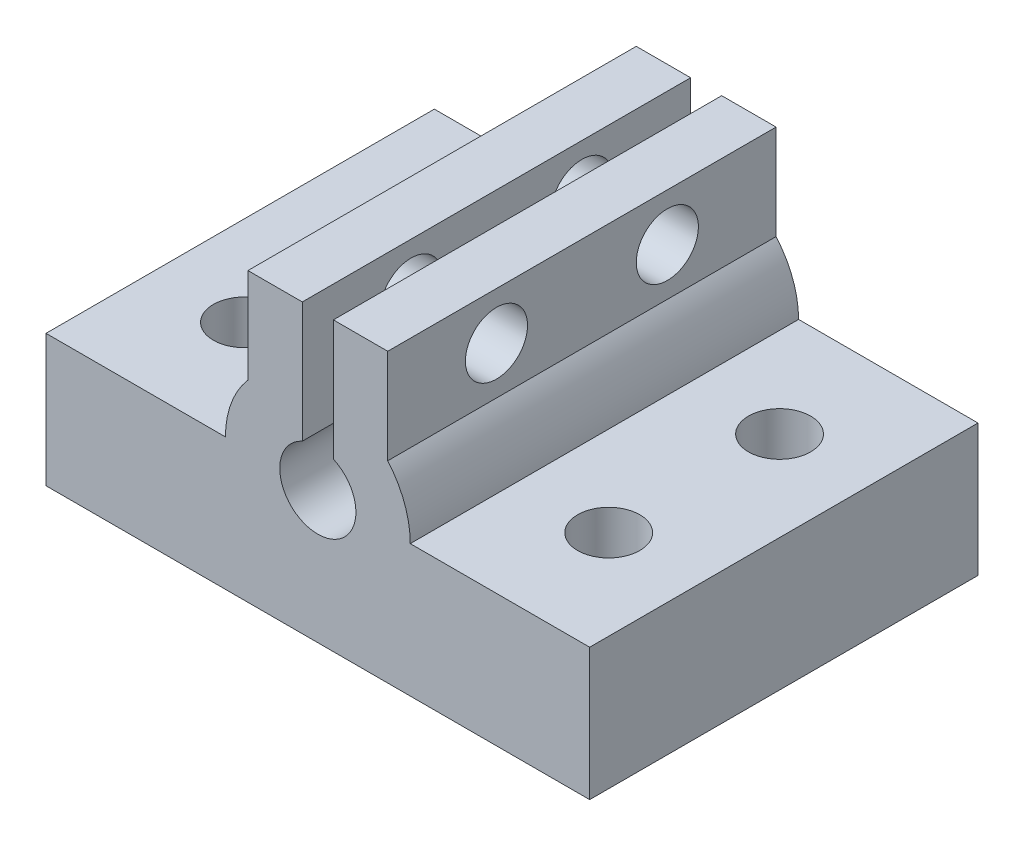
SolidWorks part; units mm, degrees
ref_plane "Front Plane" through (0, 0, 0) normal (0, 0, 1) x (1, 0, 0)
ref_plane "Top Plane" through (0, 0, 0) normal (0, 1, 0) x (1, 0, 0)
ref_plane "Right Plane" through (0, 0, 0) normal (1, 0, 0) x (0, 0, -1)
sketch "Sketch1" plane through (0, 0, 0) normal (0, 0, 1) x (1, 0, 0)
  line L0 (0, 0) -> (35, 0)
  line L1 (35, 0) -> (35, 8.5)
  line L2 (35, 8.5) -> (23.45, 8.5)
  line L3 (11.55, 8.5) -> (0, 8.5)
  line L4 (0, 8.5) -> (0, 0)
  line L5 (13, 12.3926) -> (13, 18.5)
  line L6 (13, 18.5) -> (16.5, 18.5)
  line L7 (16.5, 18.5) -> (16.5, 10.7366)
  line L8 (17.5, 0) -> (17.5, 18.5) construction
  line L9 (18.5, 10.7366) -> (18.5, 18.5)
  line L10 (18.5, 18.5) -> (22, 18.5)
  line L11 (22, 18.5) -> (22, 12.3926)
  arc A0 (23.45, 8.5) -> (22, 12.3926) centre (17.5, 8.5) ccw
  arc A1 (13, 12.3926) -> (11.55, 8.5) centre (17.5, 8.5) ccw
  arc A2 (16.5, 10.7366) -> (18.5, 10.7366) centre (17.5, 8.5) ccw
  dimension "D1" = 4.9
  dimension "D4" = 10
  dimension "D6" = 3.5
  dimension "D2" = 35
  dimension "D3" = 8.5
  dimension "D5" = 3.5
  dimension "D7" = 2
extrude "Boss-Extrude1" add sketch "Sketch1" along normal blind 25
sketch "Sketch2" plane through (22, 0, 0) normal (1, 0, 0) x (0, 0, -1)
  line L0 (-25, 15.4463) -> (0, 15.4463) construction
  line L1 (-25, 12.3926) -> (-25, 18.5) construction
  line L2 (0, 12.3926) -> (0, 18.5) construction
  circle A0 centre (-18, 15.4463) radius 2
  circle A1 centre (-7, 15.4463) radius 2
  dimension "D3" = 4
  dimension "D1" = 7
  dimension "D2" = 7
extrude "Cut-Extrude1" cut sketch "Sketch2" against normal up to surface (9 mm away) up to face at (13, 15.4463, 12.5)
sketch "Sketch3" plane through (0, 8.5, 0) normal (0, 1, 0) x (1, 0, 0)
  line L0 (29.225, -25) -> (29.225, 0) construction
  line L1 (35, -25) -> (23.45, -25) construction
  line L2 (35, 0) -> (23.45, 0) construction
  line L3 (17.5, -25) -> (17.5, 0) construction
  line L4 (0, 0) -> (35, 0) construction
  line L5 (0, -25) -> (35, -25) construction
  circle A0 centre (29.225, -18) radius 2
  circle A1 centre (29.225, -7) radius 2
  circle A2 centre (5.775, -7) radius 2
  circle A3 centre (5.775, -18) radius 2
  dimension "D2" = 7
  dimension "D3" = 4
  dimension "D1" = 7
extrude "Cut-Extrude2" cut sketch "Sketch3" against normal up to next
